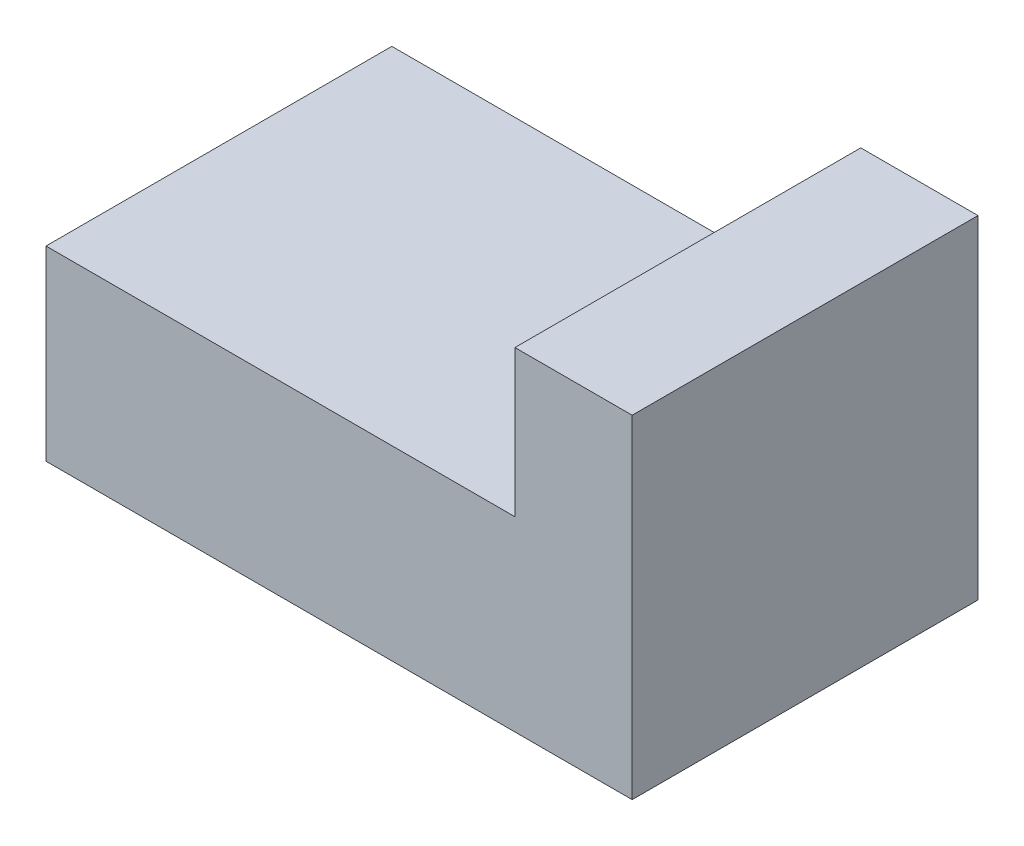
SolidWorks part; units mm, degrees
ref_plane "Front Plane" through (0, 0, 0) normal (0, 0, 1) x (1, 0, 0)
ref_plane "Top Plane" through (0, 0, 0) normal (0, 1, 0) x (1, 0, 0)
ref_plane "Right Plane" through (0, 0, 0) normal (1, 0, 0) x (0, 0, -1)
sketch "Sketch1" plane through (0, 0, 0) normal (0, 1, 0) x (1, 0, 0)
  line L1 (0, 0) -> (10, 0)
  line L2 (0, 0) -> (0, -5.9)
  line L3 (0, -5.9) -> (10, -5.9)
  line L4 (10, 0) -> (10, -5.9)
  dimension "D1" = 10
  dimension "D2" = 5.9
extrude "Boss-Extrude1" add sketch "Sketch1" along normal blind 3.18
sketch "Sketch2" plane through (0, 3.18, 0) normal (0, 1, 0) x (1, 0, 0)
  line L0 (0, -5.9) -> (10, -5.9) construction
  line L1 (10, 0) -> (8, 0)
  line L2 (10, 0) -> (10, -5.9)
  line L3 (10, -5.9) -> (8, -5.9)
  line L4 (8, 0) -> (8, -5.9)
  dimension "D1" = 2
extrude "Boss-Extrude2" add sketch "Sketch2" along normal blind 2.5
equation "\"D1@Boss-Extrude1\"=3.18"
